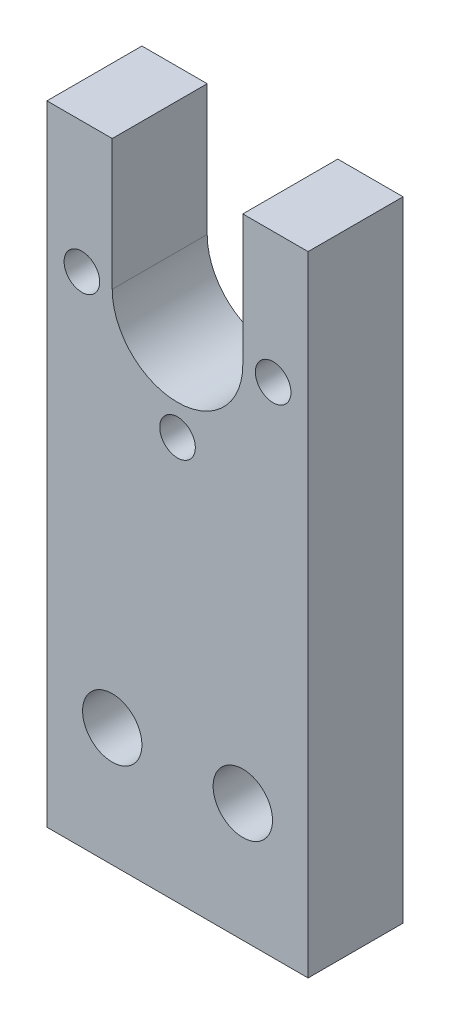
SolidWorks part; units mm, degrees
ref_plane "前视基准面" through (0, 0, 0) normal (0, 0, 1) x (1, 0, 0)
ref_plane "上视基准面" through (0, 0, 0) normal (0, 1, 0) x (1, 0, 0)
ref_plane "右视基准面" through (0, 0, 0) normal (1, 0, 0) x (0, 0, -1)
sketch "草图1" plane through (0, 0, 0) normal (0, 0, 1) x (1, 0, 0)
  line L0 (-18.0088, -9.1991) -> (3.9912, -9.1991) construction
  line L1 (-18.0088, 23.8009) -> (3.9912, 23.8009)
  line L2 (-18.0088, 23.8009) -> (-18.0088, -29.1991)
  line L3 (-18.0088, -29.1991) -> (3.9912, -29.1991)
  line L4 (3.9912, 23.8009) -> (3.9912, -29.1991)
  line L5 (-18.0088, 23.8009) -> (3.9912, -29.1991) construction
  line L6 (-18.0088, -29.1991) -> (3.9912, 23.8009) construction
  line L7 (3.9912, -9.1991) -> (-18.0088, -29.1991) construction
  line L8 (-7.0088, -9.1991) -> (-7.0088, -29.1991) construction
  line L9 (-7.0088, -29.1991) -> (-18.0088, -9.1991) construction
  line L10 (-18.0088, -9.1991) -> (-7.0088, -9.1991) construction
  line L11 (-7.0088, -9.1991) -> (-18.0088, -29.1991) construction
  line L12 (-7.0088, -9.1991) -> (3.9912, -29.1991) construction
  line L13 (3.9912, -9.1991) -> (-7.0088, -29.1991) construction
  line L14 (-7.0088, 23.8009) -> (-7.0088, 12.8009) construction
  circle A0 centre (-12.5088, -19.1991) radius 2.5
  circle A1 centre (-1.5088, -19.1991) radius 2.5
  circle A2 centre (-7.0088, 12.8009) radius 5.5
  circle A4 centre (-7.0088, 20.8589) radius 1.5
  circle A5 centre (1.0492, 12.8009) radius 1.5
  circle A6 centre (-7.0088, 4.7428) radius 1.5
  circle A7 centre (-15.0669, 12.8009) radius 1.5
  point P0 (-18.0088, -9.1991)
  dimension "D4" = 11
  dimension "D1" = 22
  dimension "D2" = 53
  dimension "D3" = 20
extrude "凸台-拉伸1" add sketch "草图1" along normal blind 8
sketch "草图2" plane through (0, 0, 8) normal (0, 0, 1) x (1, 0, 0)
  line L0 (-12.5088, 12.8009) -> (-12.5088, 23.8009)
  line L1 (3.9912, 23.8009) -> (-18.0088, 23.8009) construction
  line L2 (-12.5088, 23.8009) -> (-1.5088, 23.8009)
  line L3 (-1.5088, 23.8009) -> (-1.5088, 12.8009)
  circle A0 centre (-7.0088, 12.8009) radius 5.5 construction
  arc A1 (-1.5088, 12.8009) -> (-12.5088, 12.8009) centre (-7.0088, 12.8009) cw
extrude "切除-拉伸1" cut sketch "草图2" against normal blind 10
